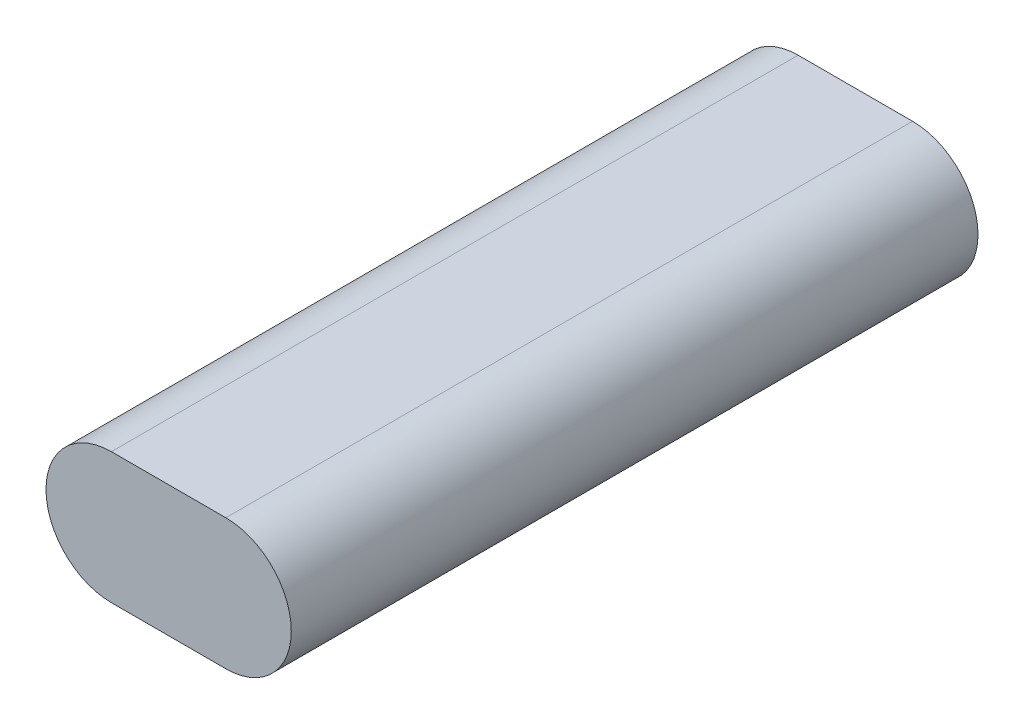
SolidWorks part; units mm, degrees
ref_plane "Front Plane" through (0, 0, 0) normal (0, 0, 1) x (1, 0, 0)
ref_plane "Top Plane" through (0, 0, 0) normal (0, 1, 0) x (1, 0, 0)
ref_plane "Right Plane" through (0, 0, 0) normal (1, 0, 0) x (0, 0, -1)
sketch "Sketch1" plane through (0, 0, 0) normal (0, 0, 1) x (1, 0, 0)
  line L0 (-13.8687, 0) -> (8.3563, 0) construction
  line L1 (-13.8687, 12.7) -> (8.3563, 12.7)
  line L2 (-13.8687, -12.7) -> (8.3563, -12.7)
  arc A0 (-13.8687, 12.7) -> (-13.8687, -12.7) centre (-13.8687, 0) ccw
  arc A1 (8.3563, -12.7) -> (8.3563, 12.7) centre (8.3563, 0) ccw
  point P3 (-2.7562, 0)
  dimension "D1" = 12.7
  dimension "D2" = 22.225
extrude "Boss-Extrude1" add sketch "Sketch1" along normal blind 133.35
